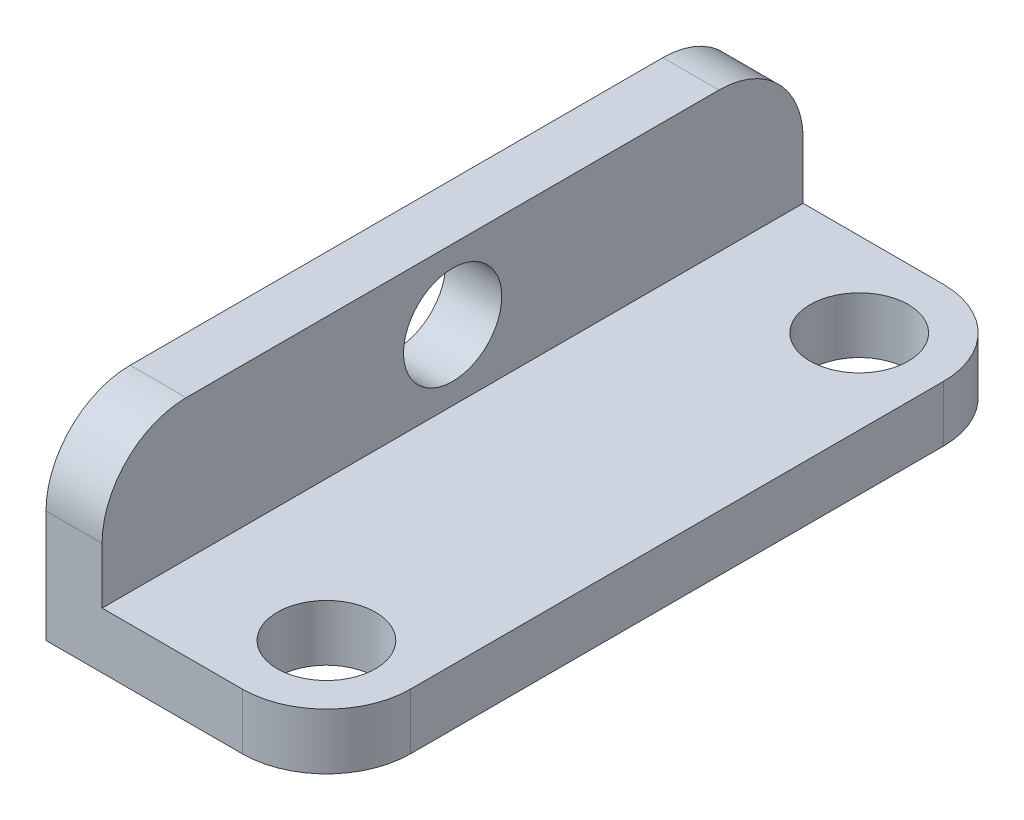
SolidWorks part; units mm, degrees
material "1023 Carbon Steel Sheet (SS)"
ref_plane "Front Plane" through (0, 0, 0) normal (0, 0, 1) x (1, 0, 0)
ref_plane "Top Plane" through (0, 0, 0) normal (0, 1, 0) x (1, 0, 0)
ref_plane "Right Plane" through (0, 0, 0) normal (1, 0, 0) x (0, 0, -1)
sketch "Sketch1" plane through (0, 0, 0) normal (0, 0, 1) x (1, 0, 0)
  line L1 (-3, 1) -> (5, 1)
  line L2 (-5, 1) -> (-5, -1)
  line L3 (-5, -1) -> (5, -1)
  line L4 (5, 1) -> (5, -1)
  line L8 (-5, 1) -> (-5, 6)
  line L9 (-5, 6) -> (-3, 6)
  line L10 (-3, 1) -> (-3, 6)
  point P0 (0, 0)
  dimension "D1" = 5
  dimension "D2" = 2
  dimension "D3" = 2
  dimension "D4" = 10
extrude "Boss-Extrude1" add sketch "Sketch1" along normal mid plane 25
fillet "Fillet1" radius 3 4 edges at (5, 0, 12.5) (5, 0, -12.5) (-4, 6, -12.5) (-4, 6, 12.5)
sketch "Sketch2" plane through (0, 1, 0) normal (0, 1, 0) x (1, 0, 0)
  line L0 (2, -12.5) -> (2, -6.8031) construction
  line L1 (5, -9.5) -> (0.4553, -9.5) construction
  line L3 (2, -12.5) -> (-3, -12.5) construction
  line L4 (-2.3102, 0) -> (9.4125, 0) construction
  circle A0 centre (2, -9.5) radius 1.75
  circle A2 centre (2, 9.5) radius 1.75
  dimension "D1" = 3.5
  dimension "D2" = 3
extrude "Cut-Extrude1" cut sketch "Sketch2" against normal through all
sketch "Sketch3" plane through (-3, 0, 0) normal (1, 0, 0) x (0, 0, -1)
  line L0 (0, 0) -> (0, 8.9515) construction
  line L1 (-9.5, 6) -> (9.5, 6) construction
  circle A0 centre (0, 3.5) radius 1.75
  dimension "D1" = 3.5
  dimension "D2" = 2.5
extrude "Cut-Extrude2" cut sketch "Sketch3" against normal through all
